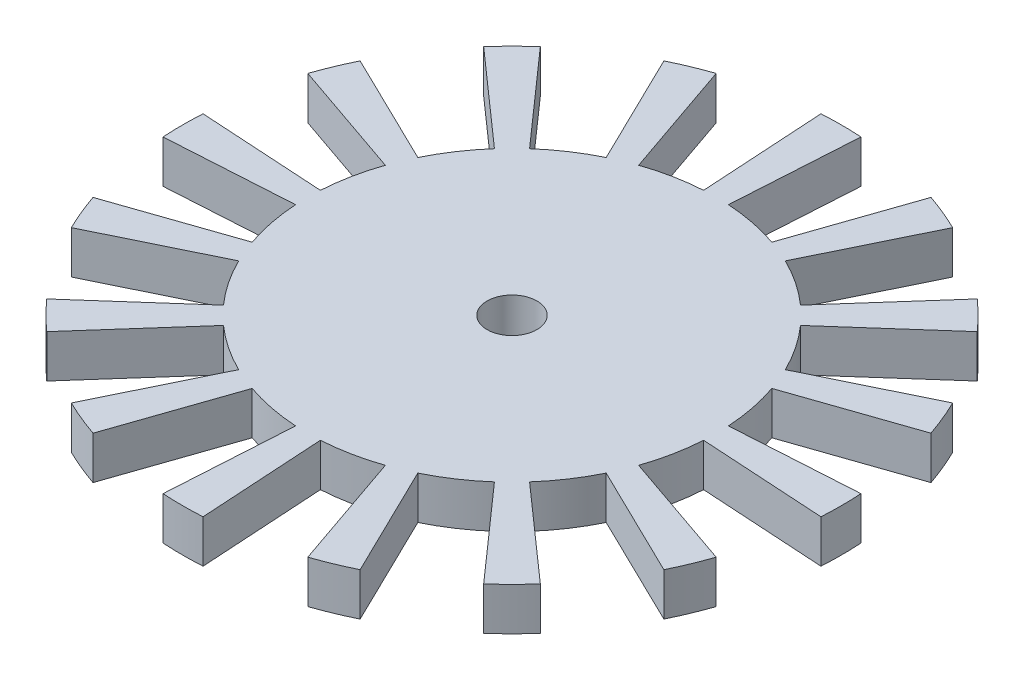
SolidWorks part; units mm, degrees
ref_plane "Front Plane" through (0, 0, 0) normal (0, 0, 1) x (1, 0, 0)
ref_plane "Top Plane" through (0, 0, 0) normal (0, 1, 0) x (1, 0, 0)
ref_plane "Right Plane" through (0, 0, 0) normal (1, 0, 0) x (0, 0, -1)
sketch "Sketch2" plane through (0, 0, 0) normal (0, 1, 0) x (1, 0, 0)
  line L18 (-17.3067, 35.5098) -> (-10.733, 22.022)
  line L20 (-2.4003, 39.4297) -> (-1.4886, 24.453)
  line L22 (12.8715, 37.3468) -> (7.9825, 23.1613)
  line L24 (26.1838, 29.5783) -> (16.2383, 18.3435)
  line L26 (35.5098, 17.3067) -> (22.022, 10.733)
  line L28 (39.4297, 2.4003) -> (24.453, 1.4886)
  line L30 (37.3468, -12.8715) -> (23.1613, -7.9825)
  line L32 (29.5783, -26.1838) -> (18.3435, -16.2383)
  line L34 (17.3067, -35.5098) -> (10.733, -22.022)
  line L36 (2.4003, -39.4297) -> (1.4886, -24.453)
  line L38 (-12.8715, -37.3468) -> (-7.9825, -23.1613)
  line L40 (-26.1838, -29.5783) -> (-16.2383, -18.3435)
  line L42 (-35.5098, -17.3067) -> (-22.022, -10.733)
  line L44 (-39.4297, -2.4003) -> (-24.453, -1.4886)
  line L46 (-37.3468, 12.8715) -> (-23.1613, 7.9825)
  line L48 (-29.5783, 26.1838) -> (-18.3435, 16.2383)
  line L82 (-15.9897, 38.6025) -> (-15.6074, 38.6695)
  line L86 (-22.022, 10.733) -> (-35.5098, 17.3067)
  line L90 (-16.2383, 18.3435) -> (-26.1838, 29.5783)
  line L94 (-7.9825, 23.1613) -> (-12.8715, 37.3468)
  line L98 (1.4886, 24.453) -> (2.4003, 39.4297)
  line L102 (10.733, 22.022) -> (17.3067, 35.5098)
  line L106 (18.3435, 16.2383) -> (29.5783, 26.1838)
  line L110 (23.1613, 7.9825) -> (37.3468, 12.8715)
  line L114 (24.453, -1.4886) -> (39.4297, -2.4003)
  line L118 (22.022, -10.733) -> (35.5098, -17.3067)
  line L122 (16.2383, -18.3435) -> (26.1838, -29.5783)
  line L126 (7.9825, -23.1613) -> (12.8715, -37.3468)
  line L130 (-1.4886, -24.453) -> (-2.4003, -39.4297)
  line L134 (-10.733, -22.022) -> (-17.3067, -35.5098)
  line L138 (-18.3435, -16.2383) -> (-29.5783, -26.1838)
  line L142 (-23.1613, -7.9825) -> (-37.3468, -12.8715)
  line L146 (-24.453, 1.4886) -> (-39.4297, 2.4003)
  circle A0 centre (0, 0) radius 2.9845
  arc A1 (-24.453, -1.4886) -> (-23.1613, -7.9825) centre (0, 0) ccw
  arc A2 (-22.022, -10.733) -> (-18.3435, -16.2383) centre (0, 0) ccw
  arc A3 (-23.1613, 7.9825) -> (-24.453, 1.4886) centre (0, 0) ccw
  arc A4 (-18.3435, 16.2383) -> (-22.022, 10.733) centre (0, 0) ccw
  arc A5 (-10.733, 22.022) -> (-16.2383, 18.3435) centre (0, 0) ccw
  arc A6 (-1.4886, 24.453) -> (-7.9825, 23.1613) centre (0, 0) ccw
  arc A7 (7.9825, 23.1613) -> (1.4886, 24.453) centre (0, 0) ccw
  arc A8 (16.2383, 18.3435) -> (10.733, 22.022) centre (0, 0) ccw
  arc A9 (22.022, 10.733) -> (18.3435, 16.2383) centre (0, 0) ccw
  arc A10 (24.453, 1.4886) -> (23.1613, 7.9825) centre (0, 0) ccw
  arc A11 (23.1613, -7.9825) -> (24.453, -1.4886) centre (0, 0) ccw
  arc A12 (18.3435, -16.2383) -> (22.022, -10.733) centre (0, 0) ccw
  arc A13 (10.733, -22.022) -> (16.2383, -18.3435) centre (0, 0) ccw
  arc A14 (1.4886, -24.453) -> (7.9825, -23.1613) centre (0, 0) ccw
  arc A15 (-7.9825, -23.1613) -> (-1.4886, -24.453) centre (0, 0) ccw
  arc A16 (-16.2383, -18.3435) -> (-10.733, -22.022) centre (0, 0) ccw
  arc A17 (39.4297, -2.4003) -> (39.4297, 2.4003) centre (0, 0) ccw
  arc A18 (35.5098, -17.3067) -> (37.3468, -12.8715) centre (0, 0) ccw
  arc A19 (26.1838, -29.5783) -> (29.5783, -26.1838) centre (0, 0) ccw
  arc A20 (12.8715, -37.3468) -> (17.3067, -35.5098) centre (0, 0) ccw
  arc A21 (-2.4003, -39.4297) -> (2.4003, -39.4297) centre (0, 0) ccw
  arc A22 (-17.3067, -35.5098) -> (-12.8715, -37.3468) centre (0, 0) ccw
  arc A23 (-29.5783, -26.1838) -> (-26.1838, -29.5783) centre (0, 0) ccw
  arc A24 (-37.3468, -12.8715) -> (-35.5098, -17.3067) centre (0, 0) ccw
  arc A25 (-39.4297, 2.4003) -> (-39.4297, -2.4003) centre (0, 0) ccw
  arc A26 (-35.5098, 17.3067) -> (-37.3468, 12.8715) centre (0, 0) ccw
  arc A27 (-26.1838, 29.5783) -> (-29.5783, 26.1838) centre (0, 0) ccw
  arc A28 (-12.8715, 37.3468) -> (-17.3067, 35.5098) centre (0, 0) ccw
  arc A29 (2.4003, 39.4297) -> (-2.4003, 39.4297) centre (0, 0) ccw
  arc A30 (17.3067, 35.5098) -> (12.8715, 37.3468) centre (0, 0) ccw
  arc A31 (29.5783, 26.1838) -> (26.1838, 29.5783) centre (0, 0) ccw
  arc A32 (37.3468, 12.8715) -> (35.5098, 17.3067) centre (0, 0) ccw
  point P39 (0, 0)
  point P73 (0, 0)
  dimension "D1" = 5.969
  dimension "D4" = 48.9966
  dimension "D7" = 16
extrude "Boss-Extrude1" add sketch "Sketch2" along normal blind 5.1308
